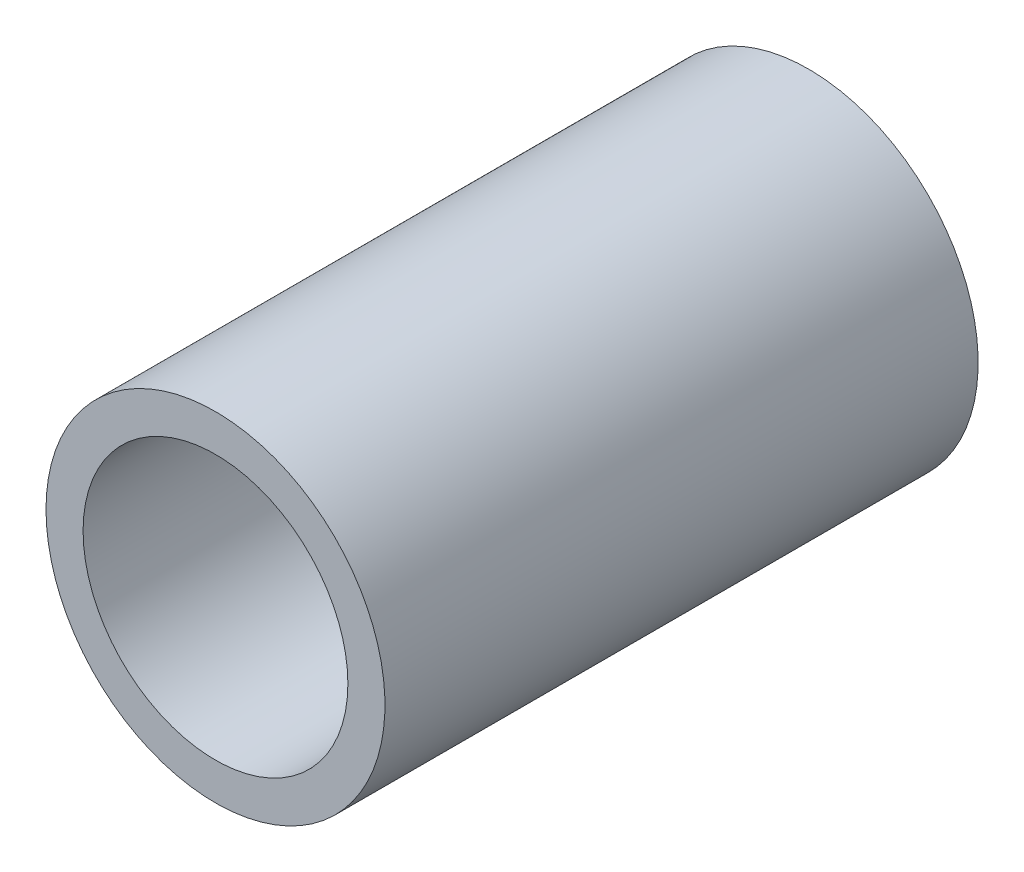
SolidWorks part; units mm, degrees
material "ASTM A36 Steel"
ref_plane "Front Plane" through (0, 0, 0) normal (0, 0, 1) x (1, 0, 0)
ref_plane "Top Plane" through (0, 0, 0) normal (0, 1, 0) x (1, 0, 0)
ref_plane "Right Plane" through (0, 0, 0) normal (1, 0, 0) x (0, 0, -1)
sketch "Sketch1" plane through (0, 0, 0) normal (0, 0, 1) x (1, 0, 0)
  circle A0 centre (0, 0) radius 8
  circle A1 centre (0, 0) radius 6.25
  dimension "D1" = 16
  dimension "D2" = 12.5
extrude "Boss-Extrude1" add sketch "Sketch1" along normal blind 28
